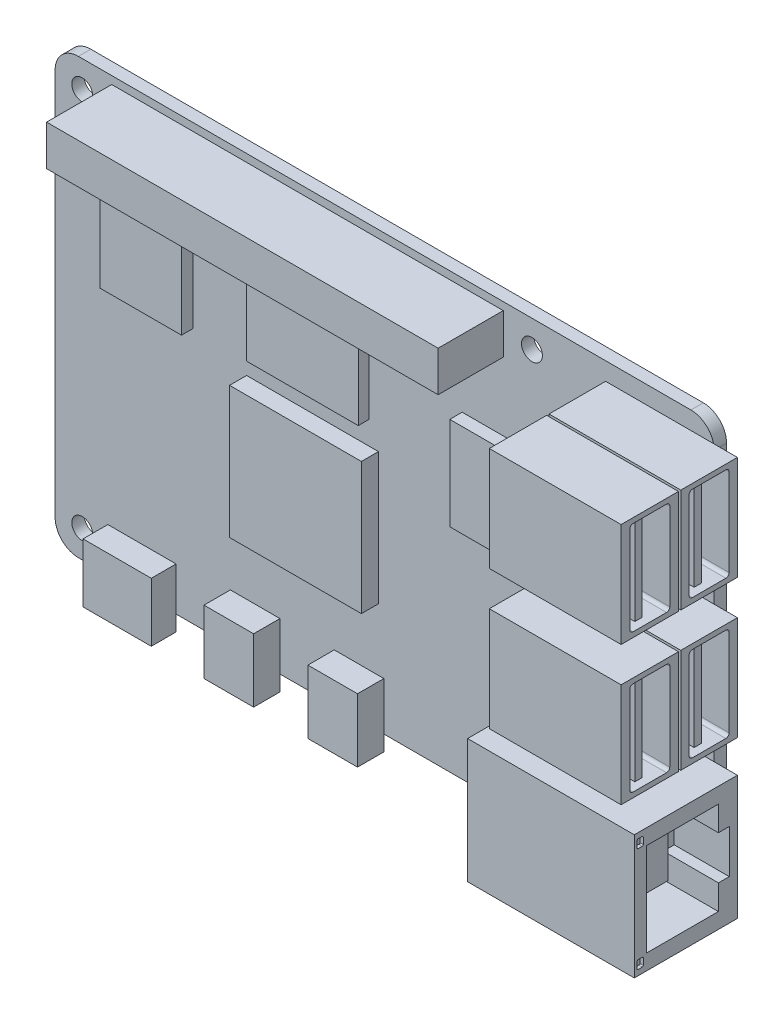
SolidWorks part; units mm, degrees
ref_plane "前视基准面" through (0, 0, 0) normal (0, 0, 1) x (1, 0, 0)
ref_plane "上视基准面" through (0, 0, 0) normal (0, 1, 0) x (1, 0, 0)
ref_plane "右视基准面" through (0, 0, 0) normal (1, 0, 0) x (0, 0, -1)
other "Configuration Table"
sketch "PCB_85x56_R3_MountPattern" plane through (0, 0, 0) normal (0, 0, 1) x (1, 0, 0)
  line L0 (-39.5, -28) -> (39.5, -28)
  line L1 (42.5, -25) -> (42.5, 25)
  line L2 (39.5, 28) -> (-39.5, 28)
  line L3 (-42.5, 25) -> (-42.5, -25)
  arc A0 (39.5, -28) -> (42.5, -25) centre (39.5, -25) ccw
  arc A1 (42.5, 25) -> (39.5, 28) centre (39.5, 25) ccw
  arc A2 (-39.5, 28) -> (-42.5, 25) centre (-39.5, 25) ccw
  arc A3 (-42.5, -25) -> (-39.5, -28) centre (-39.5, -25) ccw
  circle A4 centre (-39, -24.5) radius 1.35
  circle A5 centre (-39, 24.5) radius 1.35
  circle A6 centre (19, -24.5) radius 1.35
  circle A7 centre (19, 24.5) radius 1.35
extrude "PCB_Laminate_1p6" add sketch "PCB_85x56_R3_MountPattern" along normal blind 1.6 from offset 5.5 separate body
sketch "USB_C_Profile" plane through (0, 0, 0) normal (0, 0, 1) x (1, 0, 0)
  line L0 (-35.7, -30) -> (-26.9, -30)
  line L1 (-26.9, -30) -> (-26.9, -22.4)
  line L2 (-26.9, -22.4) -> (-35.7, -22.4)
  line L3 (-35.7, -22.4) -> (-35.7, -30)
extrude "USB_C" add sketch "USB_C_Profile" along normal blind 3.2 from offset 7.1 separate body
sketch "Micro_HDMI_1_Profile" plane through (0, 0, 0) normal (0, 0, 1) x (1, 0, 0)
  line L0 (-19.9, -30) -> (-13.5, -30)
  line L1 (-13.5, -30) -> (-13.5, -21.8)
  line L2 (-13.5, -21.8) -> (-19.9, -21.8)
  line L3 (-19.9, -21.8) -> (-19.9, -30)
extrude "Micro_HDMI_1" add sketch "Micro_HDMI_1_Profile" along normal blind 3.4 from offset 7.1 separate body
sketch "Micro_HDMI_2_Profile" plane through (0, 0, 0) normal (0, 0, 1) x (1, 0, 0)
  line L0 (-6.5, -30) -> (-0.1, -30)
  line L1 (-0.1, -30) -> (-0.1, -21.8)
  line L2 (-0.1, -21.8) -> (-6.5, -21.8)
  line L3 (-6.5, -21.8) -> (-6.5, -30)
extrude "Micro_HDMI_2" add sketch "Micro_HDMI_2_Profile" along normal blind 3.4 from offset 7.1 separate body
sketch "RJ45_Profile" plane through (0, 0, 0) normal (0, 0, 1) x (1, 0, 0)
  line L0 (24, -25.8) -> (45.5, -25.8)
  line L1 (45.5, -25.8) -> (45.5, -9.8)
  line L2 (45.5, -9.8) -> (24, -9.8)
  line L3 (24, -9.8) -> (24, -25.8)
extrude "RJ45" add sketch "RJ45_Profile" along normal blind 13.3 from offset 7.1 separate body
sketch "USB_A_1_Profile" plane through (0, 0, 0) normal (0, 0, 1) x (1, 0, 0)
  line L0 (28.5, -5.6) -> (45.5, -5.6)
  line L1 (45.5, -5.6) -> (45.5, 7.8)
  line L2 (45.5, 7.8) -> (28.5, 7.8)
  line L3 (28.5, 7.8) -> (28.5, -5.6)
extrude "USB_A_1" add sketch "USB_A_1_Profile" along normal blind 7.3 from offset 7.1 separate body
sketch "USB_A_2_Profile" plane through (0, 0, 0) normal (0, 0, 1) x (1, 0, 0)
  line L0 (28.5, -5.6) -> (45.5, -5.6)
  line L1 (45.5, -5.6) -> (45.5, 7.8)
  line L2 (45.5, 7.8) -> (28.5, 7.8)
  line L3 (28.5, 7.8) -> (28.5, -5.6)
extrude "USB_A_2" add sketch "USB_A_2_Profile" along normal blind 7.4 from offset 14.7 separate body
sketch "USB_A_3_Profile" plane through (0, 0, 0) normal (0, 0, 1) x (1, 0, 0)
  line L0 (28.5, 12.3) -> (45.5, 12.3)
  line L1 (45.5, 12.3) -> (45.5, 25.7)
  line L2 (45.5, 25.7) -> (28.5, 25.7)
  line L3 (28.5, 25.7) -> (28.5, 12.3)
extrude "USB_A_3" add sketch "USB_A_3_Profile" along normal blind 7.3 from offset 7.1 separate body
sketch "USB_A_4_Profile" plane through (0, 0, 0) normal (0, 0, 1) x (1, 0, 0)
  line L0 (28.5, 12.3) -> (45.5, 12.3)
  line L1 (45.5, 12.3) -> (45.5, 25.7)
  line L2 (45.5, 25.7) -> (28.5, 25.7)
  line L3 (28.5, 25.7) -> (28.5, 12.3)
extrude "USB_A_4" add sketch "USB_A_4_Profile" along normal blind 7.4 from offset 14.7 separate body
sketch "BCM2712_Profile" plane through (0, 0, 0) normal (0, 0, 1) x (1, 0, 0)
  line L0 (-17.8, -13.8) -> (-0.8, -13.8)
  line L1 (-0.8, -13.8) -> (-0.8, 3.2)
  line L2 (-0.8, 3.2) -> (-17.8, 3.2)
  line L3 (-17.8, 3.2) -> (-17.8, -13.8)
extrude "BCM2712" add sketch "BCM2712_Profile" along normal blind 2.2 from offset 7.1 separate body
sketch "RAM_Profile" plane through (0, 0, 0) normal (0, 0, 1) x (1, 0, 0)
  line L0 (-16.4, 6.2) -> (-2, 6.2)
  line L1 (-2, 6.2) -> (-2, 16.3)
  line L2 (-2, 16.3) -> (-16.4, 16.3)
  line L3 (-16.4, 16.3) -> (-16.4, 6.2)
extrude "RAM" add sketch "RAM_Profile" along normal blind 1.4 from offset 7.1 separate body
sketch "RP1_Profile" plane through (0, 0, 0) normal (0, 0, 1) x (1, 0, 0)
  line L0 (10, 1) -> (22, 1)
  line L1 (22, 1) -> (22, 13)
  line L2 (22, 13) -> (10, 13)
  line L3 (10, 13) -> (10, 1)
extrude "RP1" add sketch "RP1_Profile" along normal blind 1.6 from offset 7.1 separate body
sketch "Power_IC_Profile" plane through (0, 0, 0) normal (0, 0, 1) x (1, 0, 0)
  line L0 (-35.2, 5) -> (-24.7, 5)
  line L1 (-24.7, 5) -> (-24.7, 18)
  line L2 (-24.7, 18) -> (-35.2, 18)
  line L3 (-35.2, 18) -> (-35.2, 5)
extrude "Power_IC" add sketch "Power_IC_Profile" along normal blind 1.5 from offset 7.1 separate body
sketch "GPIO_Header_Profile" plane through (0, 0, 0) normal (0, 0, 1) x (1, 0, 0)
  line L0 (-35.2, 21.8) -> (15.3, 21.8)
  line L1 (15.3, 21.8) -> (15.3, 27)
  line L2 (15.3, 27) -> (-35.2, 27)
  line L3 (-35.2, 27) -> (-35.2, 21.8)
extrude "GPIO_Header" add sketch "GPIO_Header_Profile" along normal blind 8.4 from offset 7.1 separate body
sketch "Detail_USB_C_Receptacle_Profile" plane through (0, 0, 0) normal (0, 1, 0) x (1, 0, 0)
  line L0 (-34.04, -9.88) -> (-28.56, -9.88)
  line L1 (-27.42, -8.74) -> (-27.42, -8.66)
  line L2 (-28.56, -7.52) -> (-34.04, -7.52)
  line L3 (-35.18, -8.66) -> (-35.18, -8.74)
  arc A0 (-28.56, -9.88) -> (-27.42, -8.74) centre (-28.56, -8.74) ccw
  arc A1 (-27.42, -8.66) -> (-28.56, -7.52) centre (-28.56, -8.66) ccw
  arc A2 (-34.04, -7.52) -> (-35.18, -8.66) centre (-34.04, -8.66) ccw
  arc A3 (-35.18, -8.74) -> (-34.04, -9.88) centre (-34.04, -8.74) ccw
extrude "Detail_USB_C_Receptacle" cut sketch "Detail_USB_C_Receptacle_Profile" along normal blind 4.45 from offset 30.08
sketch "Detail_Micro_HDMI_Keyed_Receptacles_Profile" plane through (0, 0, 0) normal (0, 1, 0) x (1, 0, 0)
  line L0 (-19.45, -9.95) -> (-13.95, -9.95)
  line L1 (-13.95, -9.95) -> (-13.95, -8.48)
  line L2 (-13.95, -8.48) -> (-14.58, -7.65)
  line L3 (-14.58, -7.65) -> (-18.82, -7.65)
  line L4 (-18.82, -7.65) -> (-19.45, -8.48)
  line L5 (-19.45, -8.48) -> (-19.45, -9.95)
  line L6 (-6.05, -9.95) -> (-0.55, -9.95)
  line L7 (-0.55, -9.95) -> (-0.55, -8.48)
  line L8 (-0.55, -8.48) -> (-1.18, -7.65)
  line L9 (-1.18, -7.65) -> (-5.42, -7.65)
  line L10 (-5.42, -7.65) -> (-6.05, -8.48)
  line L11 (-6.05, -8.48) -> (-6.05, -9.95)
extrude "Detail_Micro_HDMI_Keyed_Receptacles" cut sketch "Detail_Micro_HDMI_Keyed_Receptacles_Profile" along normal blind 4.35 from offset 30.08
sketch "Detail_USB_A_Four_Receptacles_Profile" plane through (0, 0, 0) normal (1, 0, 0) x (0, 0, -1)
  line L0 (-12.91, -4.95) -> (-8.59, -4.95)
  line L1 (-8.17, -4.53) -> (-8.17, 6.73)
  line L2 (-8.59, 7.15) -> (-12.91, 7.15)
  line L3 (-13.33, 6.73) -> (-13.33, -4.53)
  line L4 (-20.56, -4.95) -> (-16.24, -4.95)
  line L5 (-15.82, -4.53) -> (-15.82, 6.73)
  line L6 (-16.24, 7.15) -> (-20.56, 7.15)
  line L7 (-20.98, 6.73) -> (-20.98, -4.53)
  line L8 (-12.91, 12.95) -> (-8.59, 12.95)
  line L9 (-8.17, 13.37) -> (-8.17, 24.63)
  line L10 (-8.59, 25.05) -> (-12.91, 25.05)
  line L11 (-13.33, 24.63) -> (-13.33, 13.37)
  line L12 (-20.56, 12.95) -> (-16.24, 12.95)
  line L13 (-15.82, 13.37) -> (-15.82, 24.63)
  line L14 (-16.24, 25.05) -> (-20.56, 25.05)
  line L15 (-20.98, 24.63) -> (-20.98, 13.37)
  arc A0 (-8.59, -4.95) -> (-8.17, -4.53) centre (-8.59, -4.53) ccw
  arc A1 (-8.17, 6.73) -> (-8.59, 7.15) centre (-8.59, 6.73) ccw
  arc A2 (-12.91, 7.15) -> (-13.33, 6.73) centre (-12.91, 6.73) ccw
  arc A3 (-13.33, -4.53) -> (-12.91, -4.95) centre (-12.91, -4.53) ccw
  arc A4 (-16.24, -4.95) -> (-15.82, -4.53) centre (-16.24, -4.53) ccw
  arc A5 (-15.82, 6.73) -> (-16.24, 7.15) centre (-16.24, 6.73) ccw
  arc A6 (-20.56, 7.15) -> (-20.98, 6.73) centre (-20.56, 6.73) ccw
  arc A7 (-20.98, -4.53) -> (-20.56, -4.95) centre (-20.56, -4.53) ccw
  arc A8 (-8.59, 12.95) -> (-8.17, 13.37) centre (-8.59, 13.37) ccw
  arc A9 (-8.17, 24.63) -> (-8.59, 25.05) centre (-8.59, 24.63) ccw
  arc A10 (-12.91, 25.05) -> (-13.33, 24.63) centre (-12.91, 24.63) ccw
  arc A11 (-13.33, 13.37) -> (-12.91, 12.95) centre (-12.91, 13.37) ccw
  arc A12 (-16.24, 12.95) -> (-15.82, 13.37) centre (-16.24, 13.37) ccw
  arc A13 (-15.82, 24.63) -> (-16.24, 25.05) centre (-16.24, 24.63) ccw
  arc A14 (-20.56, 25.05) -> (-20.98, 24.63) centre (-20.56, 24.63) ccw
  arc A15 (-20.98, 13.37) -> (-20.56, 12.95) centre (-20.56, 13.37) ccw
extrude "Detail_USB_A_Four_Receptacles" cut sketch "Detail_USB_A_Four_Receptacles_Profile" against normal blind 6.28 from offset 45.58
sketch "Detail_RJ45_Keyed_Receptacle_Profile" plane through (0, 0, 0) normal (1, 0, 0) x (0, 0, -1)
  line L0 (-18.8, -23.8) -> (-18.8, -11.8)
  line L1 (-18.8, -11.8) -> (-9.55, -11.8)
  line L2 (-9.55, -11.8) -> (-9.55, -15)
  line L3 (-9.55, -15) -> (-8.15, -15)
  line L4 (-8.15, -15) -> (-8.15, -20.6)
  line L5 (-8.15, -20.6) -> (-9.55, -20.6)
  line L6 (-9.55, -20.6) -> (-9.55, -23.8)
  line L7 (-9.55, -23.8) -> (-18.8, -23.8)
extrude "Detail_RJ45_Keyed_Receptacle" cut sketch "Detail_RJ45_Keyed_Receptacle_Profile" against normal blind 7.18 from offset 45.58
sketch "Detail_RJ45_LED_Pockets_Profile" plane through (0, 0, 0) normal (1, 0, 0) x (0, 0, -1)
  line L0 (-19.9, -25.1) -> (-19.38, -25.1)
  line L1 (-19.24, -24.96) -> (-19.24, -24.14)
  line L2 (-19.38, -24) -> (-19.9, -24)
  line L3 (-20.04, -24.14) -> (-20.04, -24.96)
  line L4 (-19.9, -11.6) -> (-19.38, -11.6)
  line L5 (-19.24, -11.46) -> (-19.24, -10.64)
  line L6 (-19.38, -10.5) -> (-19.9, -10.5)
  line L7 (-20.04, -10.64) -> (-20.04, -11.46)
  arc A0 (-19.38, -25.1) -> (-19.24, -24.96) centre (-19.38, -24.96) ccw
  arc A1 (-19.24, -24.14) -> (-19.38, -24) centre (-19.38, -24.14) ccw
  arc A2 (-19.9, -24) -> (-20.04, -24.14) centre (-19.9, -24.14) ccw
  arc A3 (-20.04, -24.96) -> (-19.9, -25.1) centre (-19.9, -24.96) ccw
  arc A4 (-19.38, -11.6) -> (-19.24, -11.46) centre (-19.38, -11.46) ccw
  arc A5 (-19.24, -10.64) -> (-19.38, -10.5) centre (-19.38, -10.64) ccw
  arc A6 (-19.9, -10.5) -> (-20.04, -10.64) centre (-19.9, -10.64) ccw
  arc A7 (-20.04, -11.46) -> (-19.9, -11.6) centre (-19.9, -11.46) ccw
extrude "Detail_RJ45_LED_Pockets" cut sketch "Detail_RJ45_LED_Pockets_Profile" against normal blind 1.12 from offset 45.58
sketch "USB_C_Insulated_Tongue_Profile" plane through (0, 0, 0) normal (0, 0, 1) x (1, 0, 0)
  line L0 (-34.06, -29.37) -> (-28.54, -29.37)
  line L1 (-28.54, -29.37) -> (-28.54, -25.64)
  line L2 (-28.54, -25.64) -> (-34.06, -25.64)
  line L3 (-34.06, -25.64) -> (-34.06, -29.37)
extrude "USB_C_Insulated_Tongue" add sketch "USB_C_Insulated_Tongue_Profile" along normal blind 0.52 from offset 8.44 separate body
sketch "USB_C_Gold_Contact_Row_Profile" plane through (0, 0, 0) normal (0, 0, 1) x (1, 0, 0)
  line L0 (-33.485, -28.95) -> (-33.245, -28.95)
  line L1 (-33.245, -28.95) -> (-33.245, -27.24)
  line L2 (-33.245, -27.24) -> (-33.485, -27.24)
  line L3 (-33.485, -27.24) -> (-33.485, -28.95)
  line L4 (-32.895, -28.95) -> (-32.655, -28.95)
  line L5 (-32.655, -28.95) -> (-32.655, -27.24)
  line L6 (-32.655, -27.24) -> (-32.895, -27.24)
  line L7 (-32.895, -27.24) -> (-32.895, -28.95)
  line L8 (-32.305, -28.95) -> (-32.065, -28.95)
  line L9 (-32.065, -28.95) -> (-32.065, -27.24)
  line L10 (-32.065, -27.24) -> (-32.305, -27.24)
  line L11 (-32.305, -27.24) -> (-32.305, -28.95)
  line L12 (-31.715, -28.95) -> (-31.475, -28.95)
  line L13 (-31.475, -28.95) -> (-31.475, -27.24)
  line L14 (-31.475, -27.24) -> (-31.715, -27.24)
  line L15 (-31.715, -27.24) -> (-31.715, -28.95)
  line L16 (-31.125, -28.95) -> (-30.885, -28.95)
  line L17 (-30.885, -28.95) -> (-30.885, -27.24)
  line L18 (-30.885, -27.24) -> (-31.125, -27.24)
  line L19 (-31.125, -27.24) -> (-31.125, -28.95)
  line L20 (-30.535, -28.95) -> (-30.295, -28.95)
  line L21 (-30.295, -28.95) -> (-30.295, -27.24)
  line L22 (-30.295, -27.24) -> (-30.535, -27.24)
  line L23 (-30.535, -27.24) -> (-30.535, -28.95)
  line L24 (-29.945, -28.95) -> (-29.705, -28.95)
  line L25 (-29.705, -28.95) -> (-29.705, -27.24)
  line L26 (-29.705, -27.24) -> (-29.945, -27.24)
  line L27 (-29.945, -27.24) -> (-29.945, -28.95)
  line L28 (-29.355, -28.95) -> (-29.115, -28.95)
  line L29 (-29.115, -28.95) -> (-29.115, -27.24)
  line L30 (-29.115, -27.24) -> (-29.355, -27.24)
  line L31 (-29.355, -27.24) -> (-29.355, -28.95)
extrude "USB_C_Gold_Contact_Row" add sketch "USB_C_Gold_Contact_Row_Profile" along normal blind 0.08 from offset 8.96 separate body
sketch "Micro_HDMI_1_Tongue_Profile" plane through (0, 0, 0) normal (0, 0, 1) x (1, 0, 0)
  line L0 (-18.58, -29.18) -> (-14.82, -29.18)
  line L1 (-14.82, -29.18) -> (-14.82, -25.75)
  line L2 (-14.82, -25.75) -> (-18.58, -25.75)
  line L3 (-18.58, -25.75) -> (-18.58, -29.18)
extrude "Micro_HDMI_1_Tongue" add sketch "Micro_HDMI_1_Tongue_Profile" along normal blind 0.43 from offset 8.49 separate body
sketch "Micro_HDMI_2_Tongue_Profile" plane through (0, 0, 0) normal (0, 0, 1) x (1, 0, 0)
  line L0 (-5.18, -29.18) -> (-1.42, -29.18)
  line L1 (-1.42, -29.18) -> (-1.42, -25.75)
  line L2 (-1.42, -25.75) -> (-5.18, -25.75)
  line L3 (-5.18, -25.75) -> (-5.18, -29.18)
extrude "Micro_HDMI_2_Tongue" add sketch "Micro_HDMI_2_Tongue_Profile" along normal blind 0.43 from offset 8.49 separate body
sketch "Micro_HDMI_Gold_Contact_Rows_Profile" plane through (0, 0, 0) normal (0, 0, 1) x (1, 0, 0)
  line L0 (-18.205, -28.92) -> (-18.015, -28.92)
  line L1 (-18.015, -28.92) -> (-18.015, -27.25)
  line L2 (-18.015, -27.25) -> (-18.205, -27.25)
  line L3 (-18.205, -27.25) -> (-18.205, -28.92)
  line L4 (-17.735, -28.92) -> (-17.545, -28.92)
  line L5 (-17.545, -28.92) -> (-17.545, -27.25)
  line L6 (-17.545, -27.25) -> (-17.735, -27.25)
  line L7 (-17.735, -27.25) -> (-17.735, -28.92)
  line L8 (-17.265, -28.92) -> (-17.075, -28.92)
  line L9 (-17.075, -28.92) -> (-17.075, -27.25)
  line L10 (-17.075, -27.25) -> (-17.265, -27.25)
  line L11 (-17.265, -27.25) -> (-17.265, -28.92)
  line L12 (-16.795, -28.92) -> (-16.605, -28.92)
  line L13 (-16.605, -28.92) -> (-16.605, -27.25)
  line L14 (-16.605, -27.25) -> (-16.795, -27.25)
  line L15 (-16.795, -27.25) -> (-16.795, -28.92)
  line L16 (-16.325, -28.92) -> (-16.135, -28.92)
  line L17 (-16.135, -28.92) -> (-16.135, -27.25)
  line L18 (-16.135, -27.25) -> (-16.325, -27.25)
  line L19 (-16.325, -27.25) -> (-16.325, -28.92)
  line L20 (-15.855, -28.92) -> (-15.665, -28.92)
  line L21 (-15.665, -28.92) -> (-15.665, -27.25)
  line L22 (-15.665, -27.25) -> (-15.855, -27.25)
  line L23 (-15.855, -27.25) -> (-15.855, -28.92)
  line L24 (-15.385, -28.92) -> (-15.195, -28.92)
  line L25 (-15.195, -28.92) -> (-15.195, -27.25)
  line L26 (-15.195, -27.25) -> (-15.385, -27.25)
  line L27 (-15.385, -27.25) -> (-15.385, -28.92)
  line L28 (-4.805, -28.92) -> (-4.615, -28.92)
  line L29 (-4.615, -28.92) -> (-4.615, -27.25)
  line L30 (-4.615, -27.25) -> (-4.805, -27.25)
  line L31 (-4.805, -27.25) -> (-4.805, -28.92)
  line L32 (-4.335, -28.92) -> (-4.145, -28.92)
  line L33 (-4.145, -28.92) -> (-4.145, -27.25)
  line L34 (-4.145, -27.25) -> (-4.335, -27.25)
  line L35 (-4.335, -27.25) -> (-4.335, -28.92)
  line L36 (-3.865, -28.92) -> (-3.675, -28.92)
  line L37 (-3.675, -28.92) -> (-3.675, -27.25)
  line L38 (-3.675, -27.25) -> (-3.865, -27.25)
  line L39 (-3.865, -27.25) -> (-3.865, -28.92)
  line L40 (-3.395, -28.92) -> (-3.205, -28.92)
  line L41 (-3.205, -28.92) -> (-3.205, -27.25)
  line L42 (-3.205, -27.25) -> (-3.395, -27.25)
  line L43 (-3.395, -27.25) -> (-3.395, -28.92)
  line L44 (-2.925, -28.92) -> (-2.735, -28.92)
  line L45 (-2.735, -28.92) -> (-2.735, -27.25)
  line L46 (-2.735, -27.25) -> (-2.925, -27.25)
  line L47 (-2.925, -27.25) -> (-2.925, -28.92)
  line L48 (-2.455, -28.92) -> (-2.265, -28.92)
  line L49 (-2.265, -28.92) -> (-2.265, -27.25)
  line L50 (-2.265, -27.25) -> (-2.455, -27.25)
  line L51 (-2.455, -27.25) -> (-2.455, -28.92)
  line L52 (-1.985, -28.92) -> (-1.795, -28.92)
  line L53 (-1.795, -28.92) -> (-1.795, -27.25)
  line L54 (-1.795, -27.25) -> (-1.985, -27.25)
  line L55 (-1.985, -27.25) -> (-1.985, -28.92)
extrude "Micro_HDMI_Gold_Contact_Rows" add sketch "Micro_HDMI_Gold_Contact_Rows_Profile" along normal blind 0.065 from offset 8.92 separate body
sketch "USB_A_1_Insulated_Tongue_Profile" plane through (0, 0, 0) normal (0, 0, 1) x (1, 0, 0)
  line L0 (39.38, -4.52) -> (44.9, -4.52)
  line L1 (44.9, -4.52) -> (44.9, 6.72)
  line L2 (44.9, 6.72) -> (39.38, 6.72)
  line L3 (39.38, 6.72) -> (39.38, -4.52)
extrude "USB_A_1_Insulated_Tongue" add sketch "USB_A_1_Insulated_Tongue_Profile" along normal blind 0.92 from offset 11.16 separate body
sketch "USB_A_1_Gold_Contact_Row_Profile" plane through (0, 0, 0) normal (0, 0, 1) x (1, 0, 0)
  line L0 (42.3, -2.34) -> (44.5, -2.34)
  line L1 (44.5, -2.34) -> (44.5, -1.64)
  line L2 (44.5, -1.64) -> (42.3, -1.64)
  line L3 (42.3, -1.64) -> (42.3, -2.34)
  line L4 (42.3, -0.28) -> (44.5, -0.28)
  line L5 (44.5, -0.28) -> (44.5, 0.42)
  line L6 (44.5, 0.42) -> (42.3, 0.42)
  line L7 (42.3, 0.42) -> (42.3, -0.28)
  line L8 (42.3, 1.78) -> (44.5, 1.78)
  line L9 (44.5, 1.78) -> (44.5, 2.48)
  line L10 (44.5, 2.48) -> (42.3, 2.48)
  line L11 (42.3, 2.48) -> (42.3, 1.78)
  line L12 (42.3, 3.84) -> (44.5, 3.84)
  line L13 (44.5, 3.84) -> (44.5, 4.54)
  line L14 (44.5, 4.54) -> (42.3, 4.54)
  line L15 (42.3, 4.54) -> (42.3, 3.84)
extrude "USB_A_1_Gold_Contact_Row" add sketch "USB_A_1_Gold_Contact_Row_Profile" along normal blind 0.11 from offset 11.05 separate body
sketch "USB_A_2_Insulated_Tongue_Profile" plane through (0, 0, 0) normal (0, 0, 1) x (1, 0, 0)
  line L0 (39.38, -4.52) -> (44.9, -4.52)
  line L1 (44.9, -4.52) -> (44.9, 6.72)
  line L2 (44.9, 6.72) -> (39.38, 6.72)
  line L3 (39.38, 6.72) -> (39.38, -4.52)
extrude "USB_A_2_Insulated_Tongue" add sketch "USB_A_2_Insulated_Tongue_Profile" along normal blind 0.92 from offset 18.81 separate body
sketch "USB_A_2_Gold_Contact_Row_Profile" plane through (0, 0, 0) normal (0, 0, 1) x (1, 0, 0)
  line L0 (42.3, -2.34) -> (44.5, -2.34)
  line L1 (44.5, -2.34) -> (44.5, -1.64)
  line L2 (44.5, -1.64) -> (42.3, -1.64)
  line L3 (42.3, -1.64) -> (42.3, -2.34)
  line L4 (42.3, -0.28) -> (44.5, -0.28)
  line L5 (44.5, -0.28) -> (44.5, 0.42)
  line L6 (44.5, 0.42) -> (42.3, 0.42)
  line L7 (42.3, 0.42) -> (42.3, -0.28)
  line L8 (42.3, 1.78) -> (44.5, 1.78)
  line L9 (44.5, 1.78) -> (44.5, 2.48)
  line L10 (44.5, 2.48) -> (42.3, 2.48)
  line L11 (42.3, 2.48) -> (42.3, 1.78)
  line L12 (42.3, 3.84) -> (44.5, 3.84)
  line L13 (44.5, 3.84) -> (44.5, 4.54)
  line L14 (44.5, 4.54) -> (42.3, 4.54)
  line L15 (42.3, 4.54) -> (42.3, 3.84)
extrude "USB_A_2_Gold_Contact_Row" add sketch "USB_A_2_Gold_Contact_Row_Profile" along normal blind 0.11 from offset 18.7 separate body
sketch "USB_A_3_Insulated_Tongue_Profile" plane through (0, 0, 0) normal (0, 0, 1) x (1, 0, 0)
  line L0 (39.38, 13.38) -> (44.9, 13.38)
  line L1 (44.9, 13.38) -> (44.9, 24.62)
  line L2 (44.9, 24.62) -> (39.38, 24.62)
  line L3 (39.38, 24.62) -> (39.38, 13.38)
extrude "USB_A_3_Insulated_Tongue" add sketch "USB_A_3_Insulated_Tongue_Profile" along normal blind 0.92 from offset 11.16 separate body
sketch "USB_A_3_Gold_Contact_Row_Profile" plane through (0, 0, 0) normal (0, 0, 1) x (1, 0, 0)
  line L0 (42.3, 15.56) -> (44.5, 15.56)
  line L1 (44.5, 15.56) -> (44.5, 16.26)
  line L2 (44.5, 16.26) -> (42.3, 16.26)
  line L3 (42.3, 16.26) -> (42.3, 15.56)
  line L4 (42.3, 17.62) -> (44.5, 17.62)
  line L5 (44.5, 17.62) -> (44.5, 18.32)
  line L6 (44.5, 18.32) -> (42.3, 18.32)
  line L7 (42.3, 18.32) -> (42.3, 17.62)
  line L8 (42.3, 19.68) -> (44.5, 19.68)
  line L9 (44.5, 19.68) -> (44.5, 20.38)
  line L10 (44.5, 20.38) -> (42.3, 20.38)
  line L11 (42.3, 20.38) -> (42.3, 19.68)
  line L12 (42.3, 21.74) -> (44.5, 21.74)
  line L13 (44.5, 21.74) -> (44.5, 22.44)
  line L14 (44.5, 22.44) -> (42.3, 22.44)
  line L15 (42.3, 22.44) -> (42.3, 21.74)
extrude "USB_A_3_Gold_Contact_Row" add sketch "USB_A_3_Gold_Contact_Row_Profile" along normal blind 0.11 from offset 11.05 separate body
sketch "USB_A_4_Insulated_Tongue_Profile" plane through (0, 0, 0) normal (0, 0, 1) x (1, 0, 0)
  line L0 (39.38, 13.38) -> (44.9, 13.38)
  line L1 (44.9, 13.38) -> (44.9, 24.62)
  line L2 (44.9, 24.62) -> (39.38, 24.62)
  line L3 (39.38, 24.62) -> (39.38, 13.38)
extrude "USB_A_4_Insulated_Tongue" add sketch "USB_A_4_Insulated_Tongue_Profile" along normal blind 0.92 from offset 18.81 separate body
sketch "USB_A_4_Gold_Contact_Row_Profile" plane through (0, 0, 0) normal (0, 0, 1) x (1, 0, 0)
  line L0 (42.3, 15.56) -> (44.5, 15.56)
  line L1 (44.5, 15.56) -> (44.5, 16.26)
  line L2 (44.5, 16.26) -> (42.3, 16.26)
  line L3 (42.3, 16.26) -> (42.3, 15.56)
  line L4 (42.3, 17.62) -> (44.5, 17.62)
  line L5 (44.5, 17.62) -> (44.5, 18.32)
  line L6 (44.5, 18.32) -> (42.3, 18.32)
  line L7 (42.3, 18.32) -> (42.3, 17.62)
  line L8 (42.3, 19.68) -> (44.5, 19.68)
  line L9 (44.5, 19.68) -> (44.5, 20.38)
  line L10 (44.5, 20.38) -> (42.3, 20.38)
  line L11 (42.3, 20.38) -> (42.3, 19.68)
  line L12 (42.3, 21.74) -> (44.5, 21.74)
  line L13 (44.5, 21.74) -> (44.5, 22.44)
  line L14 (44.5, 22.44) -> (42.3, 22.44)
  line L15 (42.3, 22.44) -> (42.3, 21.74)
extrude "USB_A_4_Gold_Contact_Row" add sketch "USB_A_4_Gold_Contact_Row_Profile" along normal blind 0.11 from offset 18.7 separate body
sketch "RJ45_Dark_Backpiece_Profile" plane through (0, 0, 0) normal (0, 0, 1) x (1, 0, 0)
  line L0 (38.43, -23.55) -> (39.05, -23.55)
  line L1 (39.05, -23.55) -> (39.05, -12.05)
  line L2 (39.05, -12.05) -> (38.43, -12.05)
  line L3 (38.43, -12.05) -> (38.43, -23.55)
extrude "RJ45_Dark_Backpiece" add sketch "RJ45_Dark_Backpiece_Profile" along normal blind 9.06 from offset 9.62 separate body
sketch "RJ45_Contact_Carrier_Profile" plane through (0, 0, 0) normal (0, 0, 1) x (1, 0, 0)
  line L0 (39.05, -22.8) -> (43.98, -22.8)
  line L1 (43.98, -22.8) -> (43.98, -12.8)
  line L2 (43.98, -12.8) -> (39.05, -12.8)
  line L3 (39.05, -12.8) -> (39.05, -22.8)
extrude "RJ45_Contact_Carrier" add sketch "RJ45_Contact_Carrier_Profile" along normal blind 0.7 from offset 17.75 separate body
sketch "RJ45_Eight_Gold_Contacts_Profile" plane through (0, 0, 0) normal (0, 0, 1) x (1, 0, 0)
  line L0 (40.1, -21.35) -> (44.28, -21.35)
  line L1 (44.28, -21.35) -> (44.28, -21.04)
  line L2 (44.28, -21.04) -> (40.1, -21.04)
  line L3 (40.1, -21.04) -> (40.1, -21.35)
  line L4 (40.1, -20.38) -> (44.28, -20.38)
  line L5 (44.28, -20.38) -> (44.28, -20.07)
  line L6 (44.28, -20.07) -> (40.1, -20.07)
  line L7 (40.1, -20.07) -> (40.1, -20.38)
  line L8 (40.1, -19.41) -> (44.28, -19.41)
  line L9 (44.28, -19.41) -> (44.28, -19.1)
  line L10 (44.28, -19.1) -> (40.1, -19.1)
  line L11 (40.1, -19.1) -> (40.1, -19.41)
  line L12 (40.1, -18.44) -> (44.28, -18.44)
  line L13 (44.28, -18.44) -> (44.28, -18.13)
  line L14 (44.28, -18.13) -> (40.1, -18.13)
  line L15 (40.1, -18.13) -> (40.1, -18.44)
  line L16 (40.1, -17.47) -> (44.28, -17.47)
  line L17 (44.28, -17.47) -> (44.28, -17.16)
  line L18 (44.28, -17.16) -> (40.1, -17.16)
  line L19 (40.1, -17.16) -> (40.1, -17.47)
  line L20 (40.1, -16.5) -> (44.28, -16.5)
  line L21 (44.28, -16.5) -> (44.28, -16.19)
  line L22 (44.28, -16.19) -> (40.1, -16.19)
  line L23 (40.1, -16.19) -> (40.1, -16.5)
  line L24 (40.1, -15.53) -> (44.28, -15.53)
  line L25 (44.28, -15.53) -> (44.28, -15.22)
  line L26 (44.28, -15.22) -> (40.1, -15.22)
  line L27 (40.1, -15.22) -> (40.1, -15.53)
  line L28 (40.1, -14.56) -> (44.28, -14.56)
  line L29 (44.28, -14.56) -> (44.28, -14.25)
  line L30 (44.28, -14.25) -> (40.1, -14.25)
  line L31 (40.1, -14.25) -> (40.1, -14.56)
extrude "RJ45_Eight_Gold_Contacts" add sketch "RJ45_Eight_Gold_Contacts_Profile" along normal blind 0.15 from offset 17.6 separate body
sketch "RJ45_Green_Indicator_Profile" plane through (0, 0, 0) normal (0, 0, 1) x (1, 0, 0)
  line L0 (44.55, -24.98) -> (45.18, -24.98)
  line L1 (45.18, -24.98) -> (45.18, -24.12)
  line L2 (45.18, -24.12) -> (44.55, -24.12)
  line L3 (44.55, -24.12) -> (44.55, -24.98)
extrude "RJ45_Green_Indicator" add sketch "RJ45_Green_Indicator_Profile" along normal blind 0.54 from offset 19.37 separate body
sketch "RJ45_Amber_Indicator_Profile" plane through (0, 0, 0) normal (0, 0, 1) x (1, 0, 0)
  line L0 (44.55, -11.48) -> (45.18, -11.48)
  line L1 (45.18, -11.48) -> (45.18, -10.62)
  line L2 (45.18, -10.62) -> (44.55, -10.62)
  line L3 (44.55, -10.62) -> (44.55, -11.48)
extrude "RJ45_Amber_Indicator" add sketch "RJ45_Amber_Indicator_Profile" along normal blind 0.54 from offset 19.37 separate body
